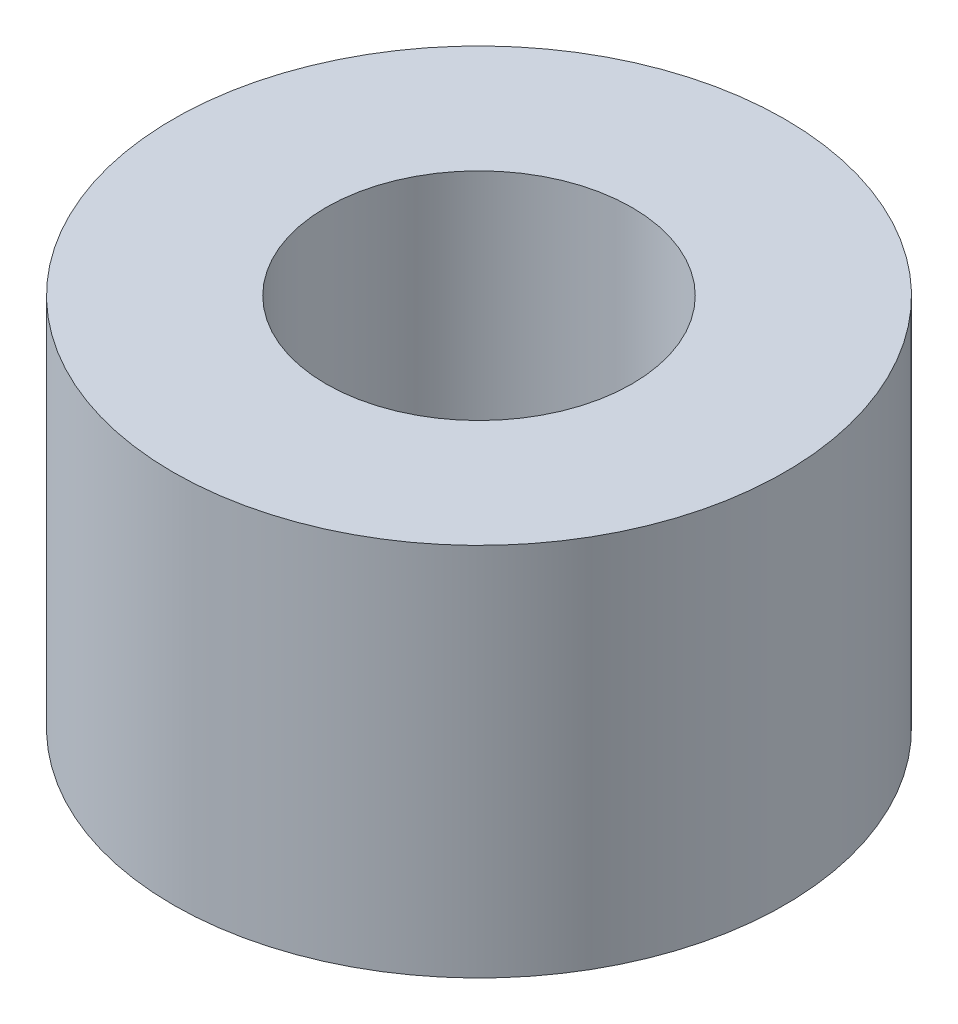
SolidWorks part; units mm, degrees
ref_plane "Front Plane" through (0, 0, 0) normal (0, 0, 1) x (1, 0, 0)
ref_plane "Top Plane" through (0, 0, 0) normal (0, 1, 0) x (1, 0, 0)
ref_plane "Right Plane" through (0, 0, 0) normal (1, 0, 0) x (0, 0, -1)
sketch "Sketch1" plane through (0, 0, 0) normal (0, 1, 0) x (1, 0, 0)
  circle A0 centre (0, 0) radius 25.4
extrude "Boss-Extrude1" add sketch "Sketch1" along normal blind 31.115
sketch "Sketch2" plane through (0, 31.115, 0) normal (0, 1, 0) x (1, 0, 0)
  circle A0 centre (0, 0) radius 12.7
extrude "Cut-Extrude1" cut sketch "Sketch2" against normal through all
